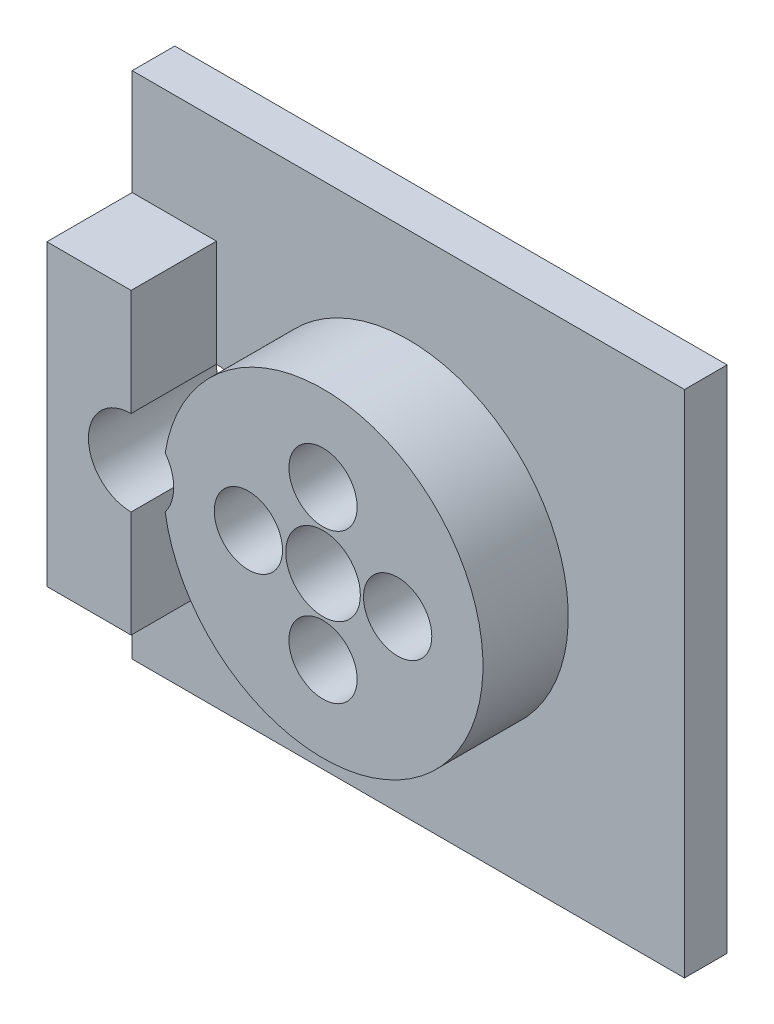
SolidWorks part; units mm, degrees
ref_plane "Front Plane" through (0, 0, 0) normal (0, 0, 1) x (1, 0, 0)
ref_plane "Top Plane" through (0, 0, 0) normal (0, 1, 0) x (1, 0, 0)
ref_plane "Right Plane" through (0, 0, 0) normal (1, 0, 0) x (0, 0, -1)
sketch "S_box1" plane through (0, 0, 0) normal (0, 0, 1) x (1, 0, 0)
  line L0 (-25.9, -23.9) -> (25.9, -23.9)
  line L1 (25.9, -23.9) -> (25.9, 23.9)
  line L2 (25.9, 23.9) -> (-25.9, 23.9)
  line L3 (-25.9, 23.9) -> (-25.9, -23.9)
  dimension "P1" = 25.9
  dimension "P2" = 23.9
  dimension "P3" = 25.9
  dimension "P4" = 23.9
  dimension "P5" = 25.9
  dimension "P6" = 23.9
  dimension "P7" = 25.9
  dimension "P8" = 23.9
extrude "Boss_1" add sketch "S_box1" along normal blind 4
ref_plane "PZ_p3_900" through (0, 0, 3.9) normal (0, 0, 1) x (1, 0, 0)
sketch "S_cyl2" plane through (0, 0, 3.9) normal (0, 0, 1) x (1, 0, 0)
  circle A0 centre (0, 0) radius 15
  dimension "D1_S_cyl2" = 30
extrude "Boss_2" add sketch "S_cyl2" along normal blind 8.1
sketch "S_box3" plane through (0, 0, 3.9) normal (0, 0, 1) x (1, 0, 0)
  line L0 (-25.9, -14) -> (-18, -14)
  line L1 (-18, -14) -> (-18, 14)
  line L2 (-18, 14) -> (-25.9, 14)
  line L3 (-25.9, 14) -> (-25.9, -14)
  dimension "P1" = 25.9
  dimension "P2" = 14
  dimension "P3" = 18
  dimension "P4" = 14
  dimension "P5" = 18
  dimension "P6" = 14
  dimension "P7" = 25.9
  dimension "P8" = 14
extrude "Boss_3" add sketch "S_box3" along normal blind 8.1
ref_plane "PZ_m0_100" through (0, 0, -0.1) normal (0, 0, 1) x (1, 0, 0)
sketch "S_hole4" plane through (0, 0, -0.1) normal (0, 0, 1) x (1, 0, 0)
  circle A0 centre (-18, 0) radius 4
  dimension "D1_S_hole4" = 8
  dimension "P2" = 18
extrude "Hole_4" cut sketch "S_hole4" along normal blind 12.2
sketch "S_hole5" plane through (0, 0, -0.1) normal (0, 0, 1) x (1, 0, 0)
  circle A0 centre (0, 0) radius 3.5
  dimension "D1_S_hole5" = 7
extrude "Hole_5" cut sketch "S_hole5" along normal blind 12.2
sketch "S_hole6" plane through (0, 0, -0.1) normal (0, 0, 1) x (1, 0, 0)
  circle A0 centre (7, 0) radius 1.7
  dimension "D1_S_hole6" = 3.4
  dimension "P2" = 7
extrude "Hole_6" cut sketch "S_hole6" along normal blind 12.2
sketch "S_hole7" plane through (0, 0, -0.1) normal (0, 0, 1) x (1, 0, 0)
  circle A0 centre (0, 7) radius 1.7
  dimension "D1_S_hole7" = 3.4
  dimension "P2" = 7
extrude "Hole_7" cut sketch "S_hole7" along normal blind 12.2
sketch "S_hole8" plane through (0, 0, -0.1) normal (0, 0, 1) x (1, 0, 0)
  circle A0 centre (-7, 0) radius 1.7
  dimension "D1_S_hole8" = 3.4
  dimension "P2" = 7
extrude "Hole_8" cut sketch "S_hole8" along normal blind 12.2
sketch "S_hole9" plane through (0, 0, -0.1) normal (0, 0, 1) x (1, 0, 0)
  circle A0 centre (0, -7) radius 1.7
  dimension "D1_S_hole9" = 3.4
  dimension "P2" = 7
extrude "Hole_9" cut sketch "S_hole9" along normal blind 12.2
ref_plane "PZ_p5_000" through (0, 0, 5) normal (0, 0, 1) x (1, 0, 0)
sketch "S_hole10" plane through (0, 0, 5) normal (0, 0, 1) x (1, 0, 0)
  circle A0 centre (7, 0) radius 3.2
  dimension "D1_S_hole10" = 6.4
  dimension "P2" = 7
extrude "Hole_10" cut sketch "S_hole10" along normal blind 7.1
sketch "S_hole11" plane through (0, 0, 5) normal (0, 0, 1) x (1, 0, 0)
  circle A0 centre (0, 7) radius 3.2
  dimension "D1_S_hole11" = 6.4
  dimension "P2" = 7
extrude "Hole_11" cut sketch "S_hole11" along normal blind 7.1
sketch "S_hole12" plane through (0, 0, 5) normal (0, 0, 1) x (1, 0, 0)
  circle A0 centre (-7, 0) radius 3.2
  dimension "D1_S_hole12" = 6.4
  dimension "P2" = 7
extrude "Hole_12" cut sketch "S_hole12" along normal blind 7.1
sketch "S_hole13" plane through (0, 0, 5) normal (0, 0, 1) x (1, 0, 0)
  circle A0 centre (0, -7) radius 3.2
  dimension "D1_S_hole13" = 6.4
  dimension "P2" = 7
extrude "Hole_13" cut sketch "S_hole13" along normal blind 7.1
ref_plane "PX_m26_000" through (-26, 0, 0) normal (1, 0, 0) x (0, 0, -1)
sketch "S_hole14" plane through (-26, 0, 0) normal (1, 0, 0) x (0, 0, -1)
  circle A0 centre (-8, -10) radius 0.9
  dimension "D1_S_hole14" = 1.8
  dimension "P2" = 8
  dimension "P3" = 10
extrude "Hole_14" cut sketch "S_hole14" along normal blind 6.1
sketch "S_hole15" plane through (-26, 0, 0) normal (1, 0, 0) x (0, 0, -1)
  circle A0 centre (-8, 10) radius 0.9
  dimension "D1_S_hole15" = 1.8
  dimension "P2" = 8
  dimension "P3" = 10
extrude "Hole_15" cut sketch "S_hole15" along normal blind 6.1
equation "\"plate_t\" = 3"
equation "\"clearance\" = 0.5"
